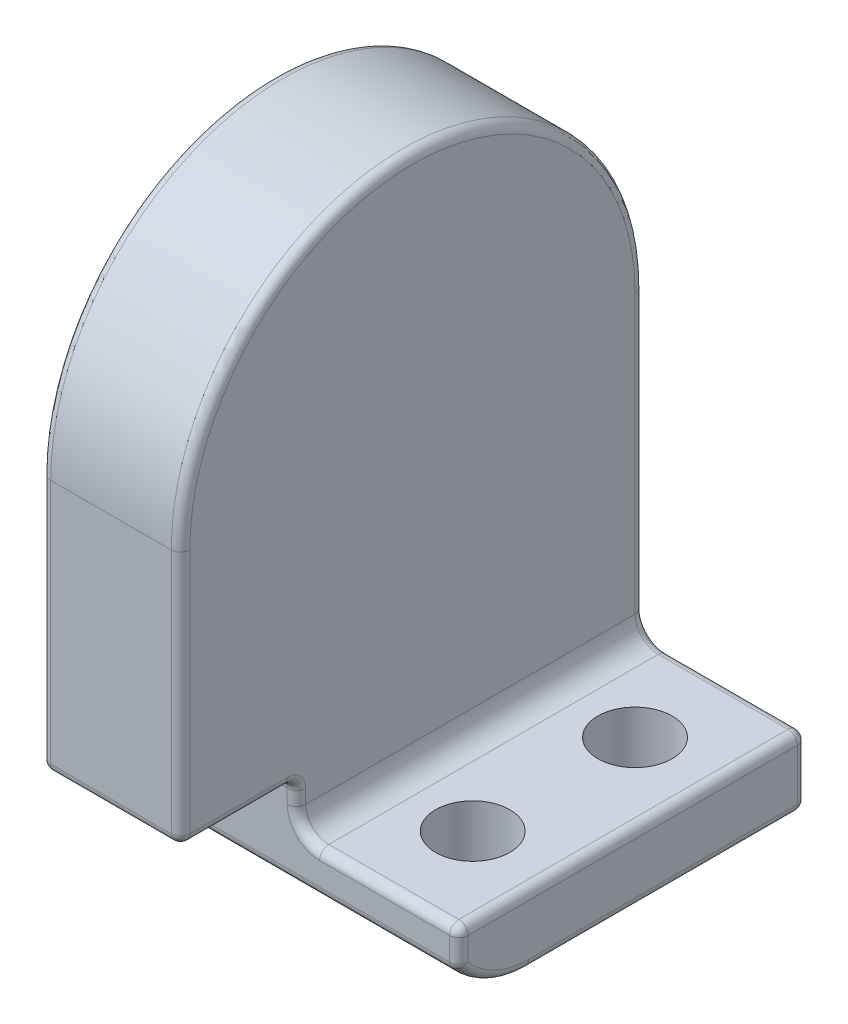
SolidWorks part; units mm, degrees
ref_plane "前视基准面" through (0, 0, 0) normal (0, 0, 1) x (1, 0, 0)
ref_plane "上视基准面" through (0, 0, 0) normal (0, 1, 0) x (1, 0, 0)
ref_plane "右视基准面" through (0, 0, 0) normal (1, 0, 0) x (0, 0, -1)
sketch "草图1" plane through (0, 0, 0) normal (1, 0, 0) x (0, 0, -1)
  line L0 (-5, 0) -> (-5, -8)
  line L1 (5, 0) -> (5, -8)
  line L2 (5, -8) -> (-5, -8)
  circle A0 centre (0, 0) radius 3
  arc A1 (5, 0) -> (-5, 0) centre (0, 0) ccw
extrude "凸台-拉伸1" add sketch "草图1" along normal blind 3
sketch "草图2" plane through (0, -8, 0) normal (0, -1, 0) x (1, 0, 0)
  line L0 (3, 5) -> (3, -5) construction
  line L1 (6.5, -5) -> (3, -5)
  line L2 (3, -5) -> (3, 5)
  line L3 (6.5, 5) -> (3, 5)
  line L8 (6.5, -5) -> (6.5, 5)
  circle A0 centre (4.8, -3) radius 0.8
  circle A1 centre (4.8, 0.5) radius 0.8
  dimension "D1" = 5.5
  dimension "D3" = 0
  dimension "D5" = 1.8
  dimension "D6" = 1.6
  dimension "D8" = 2
  dimension "D4" = 1.6
  dimension "D2" = 3.5
extrude "凸台-拉伸2" add sketch "草图2" against normal blind 1.5
sketch "草图3" plane through (3, 0, 0) normal (1, 0, 0) x (0, 0, -1)
  circle A0 centre (0, 0) radius 3.9779
sketch "草图5" plane through (0, -8, 0) normal (0, -1, 0) x (1, 0, 0)
  line L0 (6.5, -5) -> (6.5, 5) construction
  line L1 (0, 5) -> (0, -5) construction
  line L2 (0, 5) -> (6.5, 5)
  line L3 (0, 5) -> (0, 2.5)
  line L5 (0, 2.5) -> (6.5, 2.5)
  line L6 (6.5, 5) -> (6.5, 2.5)
  dimension "D1" = 2.5
  dimension "D2" = 0
extrude "切除-拉伸1" cut sketch "草图5" against normal blind 2.5
sketch "草图6" plane through (0, 0, 0) normal (-1, 0, 0) x (0, 0, 1)
  line L2 (2.8974, -6) -> (3.2771, -6)
  line L3 (1, -8) -> (1, -8.3251)
  line L4 (1, -8.3251) -> (3.2771, -8.3251)
  line L5 (3.2771, -6) -> (3.2771, -8.3251)
  arc A0 (1, -8) -> (2.8974, -6) centre (1, -6.1) ccw
extrude "切除-拉伸2" cut sketch "草图6" against normal up to next
fillet "圆角1" radius 0.5 1 edges at (3, -6.5, -1.25)
fillet "圆角2" radius 0.2 25 edges at (5, -6.5, -5) (3.1464, -6.3536, -5) (3, -3, -5) (3, -2.75, 5) (0, -4, -5) (0, -2.75, 5) (6.5, -8, -2) (6.5, -6.5, -1.25) (6.5, -7.25, -5) (3, 5, 0) (0, 5, 0) (3, -5.5, 3.75) (0, -5.5, 3.75) (1.5, -5.5, 5) (6.5, -7.8067, 1.8349) (3.25, -8, -5) (5, -6.5, 2.5) (3.1464, -6.3536, 2.5) (0, -6.3831, 2.5) (3, -5.75, 2.5) (3.25, -7.2662, 2.5) (6.5, -6.8831, 2.5) (1.5, -5.5, 2.5) (0, -7.8067, 1.8349) (0, -8, -2)
chamfer "倒角1" distance 0.2 angle 45 2 edges at (0, 0, -3) (3, 0, -3)
extrude "凸台-拉伸3" add sketch "草图3" against normal blind 0.4
